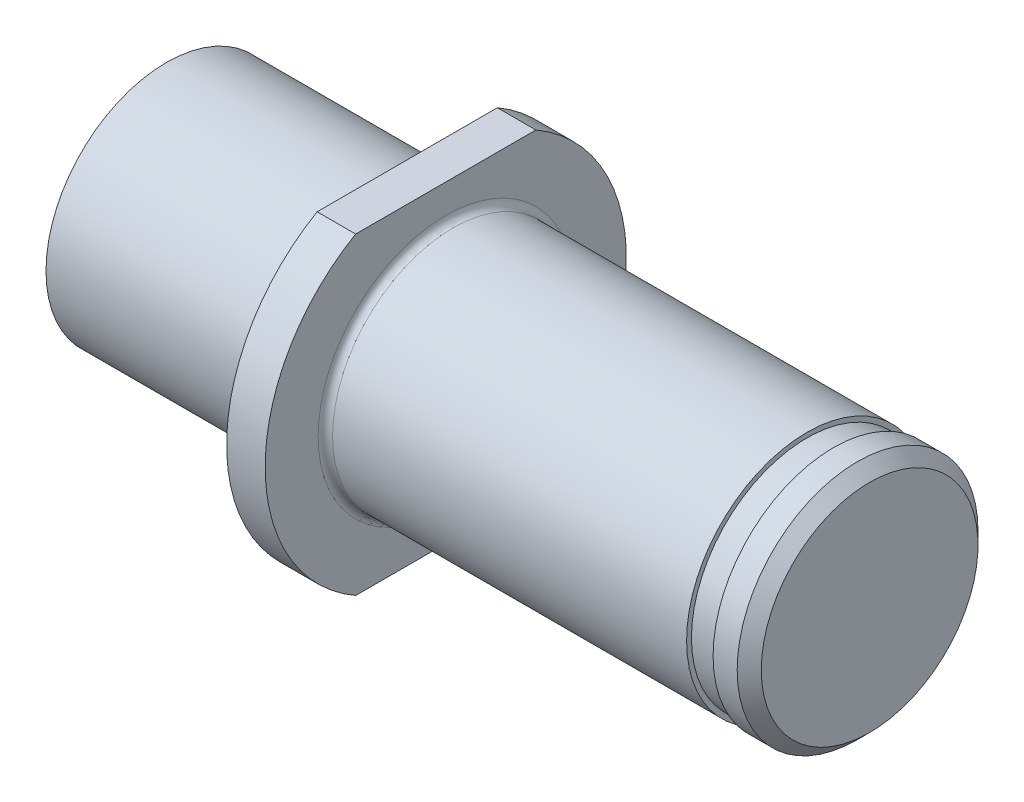
SolidWorks part; units mm, degrees
material "1.4301 (X5CrNi18-10)"
ref_plane "Vorne" through (0, 0, 0) normal (0, 0, 1) x (1, 0, 0)
ref_plane "Oben" through (0, 0, 0) normal (0, 1, 0) x (1, 0, 0)
ref_plane "Rechts" through (0, 0, 0) normal (1, 0, 0) x (0, 0, -1)
sketch "Skizze1" plane through (0, 0, 0) normal (0, 0, 1) x (1, 0, 0)
  line L0 (-55.6715, 0) -> (46.4815, 0) construction
  line L1 (14.3, 4.8) -> (15.4, 4.8)
  line L2 (15.4, 4.8) -> (15.4, 5)
  line L3 (15.4, 5) -> (16.4, 5)
  line L4 (16.9, 4.5) -> (16.9, 0)
  line L5 (-12.3, 0) -> (-12.3, 5)
  line L6 (-12.3, 5) -> (-3.05, 5)
  line L7 (-2.3, 4.25) -> (-2.3, 7.5)
  line L8 (-2.3, 7.5) -> (-0.7, 7.5)
  line L9 (-0.7, 7.5) -> (-0.7, 5.3)
  line L10 (16.9, 0) -> (-12.3, 0)
  line L11 (-0.4, 5) -> (14.3, 5)
  line L12 (14.3, 5) -> (14.3, 4.8)
  line L13 (-3.05, 5) -> (-3.05, 4.25)
  line L14 (-3.05, 4.25) -> (-2.3, 4.25)
  line L15 (16.4, 5) -> (16.9, 4.5)
  arc A0 (-0.7, 5.3) -> (-0.4, 5) centre (-0.4, 5.3) ccw
  point P8 (16.9, 5)
  point P17 (-0.7, 5)
  dimension "D13" = 0.3
  dimension "D2" = 10
  dimension "D3" = 1.1
  dimension "D4" = 1.5
  dimension "D5" = 10
  dimension "D6" = 15
  dimension "D7" = 10
  dimension "D8" = 1.6
  dimension "D9" = 10
  dimension "D10" = 15
  dimension "D11" = 2.3
  dimension "D12" = 9.6
  dimension "D14" = 8.5
  dimension "D15" = 0.75
  dimension "D16" = 29.2
revolve "Rotation1" add sketch "Skizze1" angle 360 about L0
cosmetic thread "Gewindedarstellung1" parameters "D1"=10, "D2"=8.344
sketch "Skizze5" plane through (0, 0, 0) normal (1, 0, 0) x (0, 0, -1)
  line L1 (-3.7417, 6.5) -> (3.7417, 6.5)
  line L3 (-3.7417, -6.5) -> (3.7417, -6.5)
  arc A0 (3.7417, 6.5) -> (-3.7417, 6.5) centre (0, 0) ccw
  arc A1 (-3.7417, -6.5) -> (3.7417, -6.5) centre (0, 0) ccw
  dimension "D5" = 15
  dimension "D1" = 13
  dimension "D2" = 6.5
extrude "Schnitt-Linear austragen2" cut sketch "Skizze5" against normal mid plane 15
